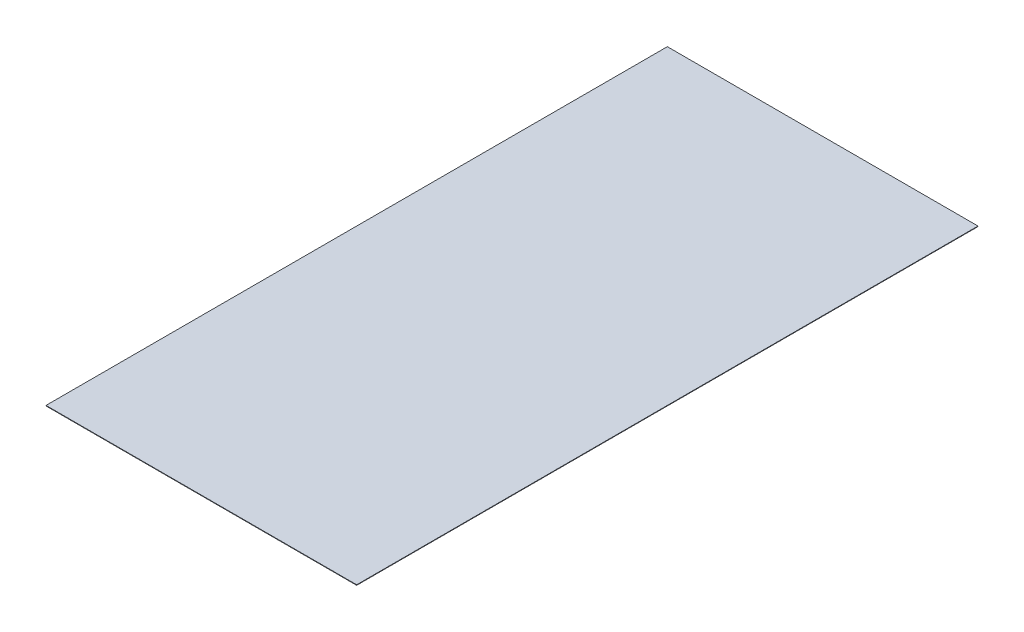
SolidWorks part; units mm, degrees
material "ASTM A36 Acero"
ref_plane "Alzado" through (0, 0, 0) normal (0, 0, 1) x (1, 0, 0)
ref_plane "Planta" through (0, 0, 0) normal (0, 1, 0) x (1, 0, 0)
ref_plane "Vista lateral" through (0, 0, 0) normal (1, 0, 0) x (0, 0, -1)
sketch "Croquis1" plane through (0, 0, 0) normal (0, 1, 0) x (1, 0, 0)
  line L1 (-609.6, -1219.2) -> (609.6, -1219.2)
  line L2 (-609.6, -1219.2) -> (-609.6, 1219.2)
  line L3 (-609.6, 1219.2) -> (609.6, 1219.2)
  line L4 (609.6, -1219.2) -> (609.6, 1219.2)
  line L5 (-609.6, -1219.2) -> (609.6, 1219.2) construction
  line L6 (-609.6, 1219.2) -> (609.6, -1219.2) construction
  point P0 (0, 0)
  dimension "D1" = 2438.4
  dimension "D2" = 1219.2
extrude "Saliente-Extruir1" add sketch "Croquis1" along normal blind 1.9
